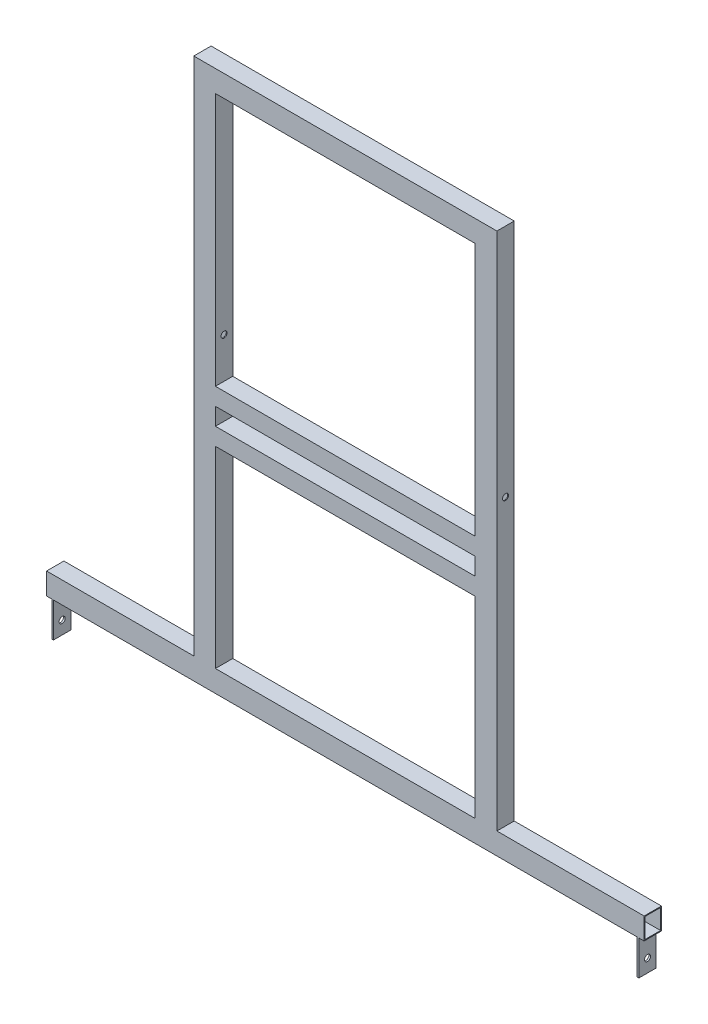
SolidWorks part; units mm, degrees
ref_plane "Front Plane" through (0, 0, 0) normal (0, 0, 1) x (1, 0, 0)
ref_plane "Top Plane" through (0, 0, 0) normal (0, 1, 0) x (1, 0, 0)
ref_plane "Right Plane" through (0, 0, 0) normal (1, 0, 0) x (0, 0, -1)
sketch "Sketch2" plane through (0, 0, 0) normal (0, 0, 1) x (1, 0, 0)
  line L0 (-19.0758, -602.1102) -> (-189.0758, -602.1102)
  line L1 (-19.0758, -2.1102) -> (330.9242, -2.1102)
  line L2 (-19.0758, -2.1102) -> (-19.0758, -602.1102)
  line L3 (-189.0758, -602.1102) -> (-189.0758, -627.1102)
  line L4 (330.9242, -2.1102) -> (330.9242, -602.1102)
  line L5 (-189.0758, -627.1102) -> (500.9242, -627.1102)
  line L6 (500.9242, -627.1102) -> (500.9242, -602.1102)
  line L7 (500.9242, -602.1102) -> (330.9242, -602.1102)
  line L8 (5.9242, -27.1102) -> (5.9242, -319.9053)
  line L9 (5.9242, -602.1102) -> (5.9242, -602.1102)
  line L10 (5.9242, -602.1102) -> (5.9242, -602.1102)
  line L11 (5.9242, -602.1102) -> (305.9242, -602.1102)
  line L12 (305.9242, -602.1102) -> (305.9242, -602.1102)
  line L13 (305.9242, -602.1102) -> (305.9242, -602.1102)
  line L14 (305.9242, -27.1102) -> (305.9242, -319.9053)
  line L15 (5.9242, -27.1102) -> (305.9242, -27.1102)
  line L16 (5.9242, -319.9053) -> (305.9242, -319.9053)
  line L17 (5.9242, -359.9053) -> (305.9242, -359.9053)
  line L18 (5.9242, -379.9053) -> (5.9242, -602.1102)
  line L19 (5.9242, -379.9053) -> (305.9242, -379.9053)
  line L20 (305.9242, -379.9053) -> (305.9242, -602.1102)
  line L21 (5.9242, -339.9053) -> (305.9242, -339.9053)
  line L22 (305.9242, -339.9053) -> (305.9242, -359.9053)
  line L23 (5.9242, -339.9053) -> (5.9242, -359.9053)
  line L24 (305.9242, -27.1102) -> (305.9242, -602.1102) construction
  line L26 (5.9242, -27.1102) -> (5.9242, -602.1102) construction
  dimension "D1" = 350
  dimension "D2" = 600
  dimension "D3" = 690
  dimension "D4" = 170
  dimension "D5" = 25
  dimension "D7" = 222.2049
  dimension "D8" = 20
  dimension "D10" = 25
  dimension "D6" = 25
  dimension "D9" = 2
extrude "Boss-Extrude1" add sketch "Sketch2" along normal blind 20
shell "Shell1" thickness 1
sketch "Sketch3" plane through (0, -627.1102, 0) normal (0, -1, 0) x (1, 0, 0)
  line L0 (492.9242, 20) -> (492.9242, 0)
  line L1 (-189.0758, 20) -> (500.9242, 20) construction
  line L2 (-183.0758, 20) -> (-181.0758, 20)
  line L3 (-183.0758, 20) -> (-183.0758, 0)
  line L4 (-183.0758, 0) -> (-181.0758, 0)
  line L5 (494.9242, 20) -> (494.9242, 0)
  line L6 (492.9242, 20) -> (494.9242, 20)
  line L7 (492.9242, 0) -> (494.9242, 0)
  line L8 (-189.0758, 20) -> (-189.0758, 0) construction
  line L9 (-181.0758, 20) -> (-181.0758, 0)
  line L10 (-189.0758, 0) -> (500.9242, 0) construction
  line L11 (500.9242, 20) -> (500.9242, 0) construction
  dimension "D1" = 2
  dimension "D3" = 6
  dimension "D4" = 6
  dimension "D2" = 2
extrude "Boss-Extrude2" add sketch "Sketch3" along normal blind 40
sketch "Sketch4" plane through (-189.0758, 0, 0) normal (-1, 0, 0) x (0, 0, 1)
  line L0 (20, -667.1102) -> (0, -667.1102) construction
  line L1 (0, -602.1102) -> (0, -627.1102) construction
  circle A0 centre (10, -652.1102) radius 3.5
  dimension "D3" = 7
  dimension "D1" = 15
  dimension "D2" = 10
extrude "Cut-Extrude1" cut sketch "Sketch4" against normal through all both and the other way through all
sketch "Sketch5" plane through (-19.0758, 0, 0) normal (-1, 0, 0) x (0, 0, 1)
  line L0 (20, -2.1102) -> (0, -2.1102) construction
  line L1 (20, -2.1102) -> (20, -602.1102) construction
  line L2 (0, -2.1102) -> (0, -602.1102) construction
  circle A0 centre (10, -273.2002) radius 3.5
  dimension "D1" = 7
  dimension "D2" = 271.09
  dimension "D3" = 20
extrude "Cut-Extrude2" cut sketch "Sketch5" against normal through all both and the other way through all
